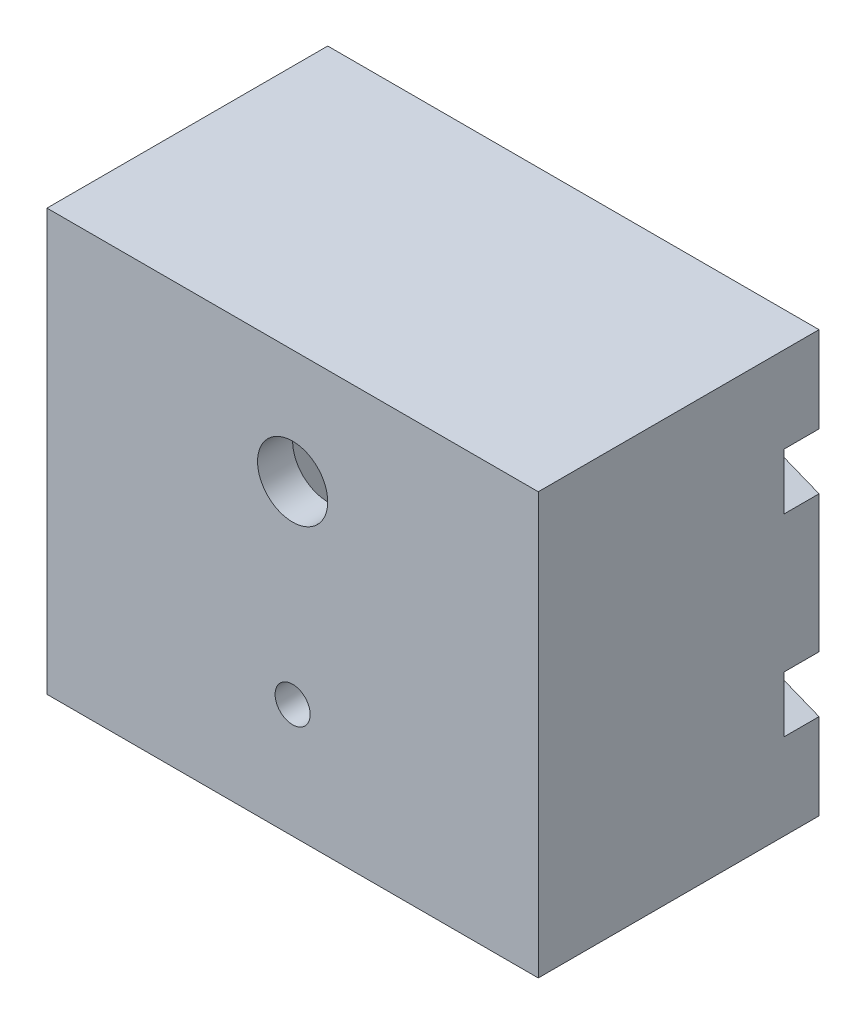
SolidWorks part; units mm, degrees
ref_plane "Front Plane" through (0, 0, 0) normal (0, 0, 1) x (1, 0, 0)
ref_plane "Top Plane" through (0, 0, 0) normal (0, 1, 0) x (1, 0, 0)
ref_plane "Right Plane" through (0, 0, 0) normal (1, 0, 0) x (0, 0, -1)
sketch "Sketch1" plane through (0, 0, 0) normal (0, 0, 1) x (1, 0, 0)
  line L1 (0, 0) -> (44.45, 0)
  line L2 (0, 0) -> (0, 38.1)
  line L3 (0, 38.1) -> (44.45, 38.1)
  line L4 (44.45, 0) -> (44.45, 38.1)
extrude "Boss-Extrude1" add sketch "Sketch1" along normal blind 25.4
sketch "Sketch2" plane through (0, 0, 0) normal (0, 0, -1) x (-1, 0, 0)
  line L0 (-44.45, 19.05) -> (-41.275, 19.05) construction
  line L1 (-44.45, 0) -> (-44.45, 38.1) construction
  line L2 (0, 19.05) -> (-3.175, 19.05) construction
  line L3 (0, 38.1) -> (0, 0) construction
  line L4 (-22.225, 38.1) -> (-22.225, 34.925) construction
  line L5 (-44.45, 38.1) -> (0, 38.1) construction
  line L6 (-22.225, 0) -> (-22.225, 3.175) construction
  line L7 (0, 0) -> (-44.45, 0) construction
  line L9 (-41.275, 3.175) -> (-3.175, 3.175)
  line L10 (-41.275, 3.175) -> (-41.275, 34.925)
  line L11 (-41.275, 34.925) -> (-3.175, 34.925)
  line L12 (-3.175, 3.175) -> (-3.175, 34.925)
extrude "Cut-Extrude1" cut sketch "Sketch2" against normal blind 22.225
sketch "Sketch3" plane through (0, 0, 25.4) normal (0, 0, 1) x (1, 0, 0)
  line L0 (0, 19.05) -> (44.45, 19.05) construction
  line L1 (0, 38.1) -> (0, 0) construction
  line L2 (44.45, 0) -> (44.45, 38.1) construction
  line L3 (22.225, 19.05) -> (22.225, 27.7812) construction
  line L4 (22.225, 19.05) -> (22.225, 10.3188) construction
  circle A0 centre (22.225, 27.7812) radius 3.175
  circle A1 centre (22.225, 10.3188) radius 1.5875
  dimension "D1" = 6.35
  dimension "D2" = 3.175
extrude "Cut-Extrude2" cut sketch "Sketch3" against normal blind 22.225
sketch "Sketch4" plane through (0, 0, 0) normal (0, 0, -1) x (-1, 0, 0)
  line L0 (-44.45, 19.05) -> (0, 19.05) construction
  line L1 (-44.45, 0) -> (-44.45, 38.1) construction
  line L2 (0, 38.1) -> (0, 0) construction
  line L3 (-22.225, 27.7812) -> (-44.45, 27.7812) construction
  line L4 (-22.225, 10.3188) -> (-44.45, 10.3187) construction
  line L7 (-41.275, 26.5112) -> (-41.275, 29.0512)
  line L8 (-41.275, 34.925) -> (-41.275, 3.175) construction
  line L9 (-44.45, 25.2412) -> (-41.275, 26.5112)
  line L10 (-41.275, 29.0512) -> (-44.45, 30.3212)
  line L11 (-44.45, 25.2412) -> (-44.45, 30.3212)
  line L12 (-22.225, 10.3188) -> (-22.225, 27.7812) construction
  line L13 (-44.45, 12.8587) -> (-41.275, 11.5887)
  line L14 (-41.275, 11.5887) -> (-41.275, 9.0487)
  line L15 (-41.275, 9.0487) -> (-44.45, 7.7787)
  line L16 (-44.45, 12.8587) -> (-44.45, 7.7787)
  line L17 (0, 25.2412) -> (-3.175, 26.5112)
  line L18 (-3.175, 26.5112) -> (-3.175, 29.0512)
  line L19 (-3.175, 29.0512) -> (0, 30.3212)
  line L20 (0, 25.2412) -> (0, 30.3212)
  line L21 (0, 12.8587) -> (0, 7.7787)
  line L22 (-3.175, 9.0487) -> (0, 7.7787)
  line L23 (-3.175, 11.5887) -> (-3.175, 9.0487)
  line L24 (0, 12.8587) -> (-3.175, 11.5887)
extrude "Cut-Extrude3" cut sketch "Sketch4" against normal blind 3.175
